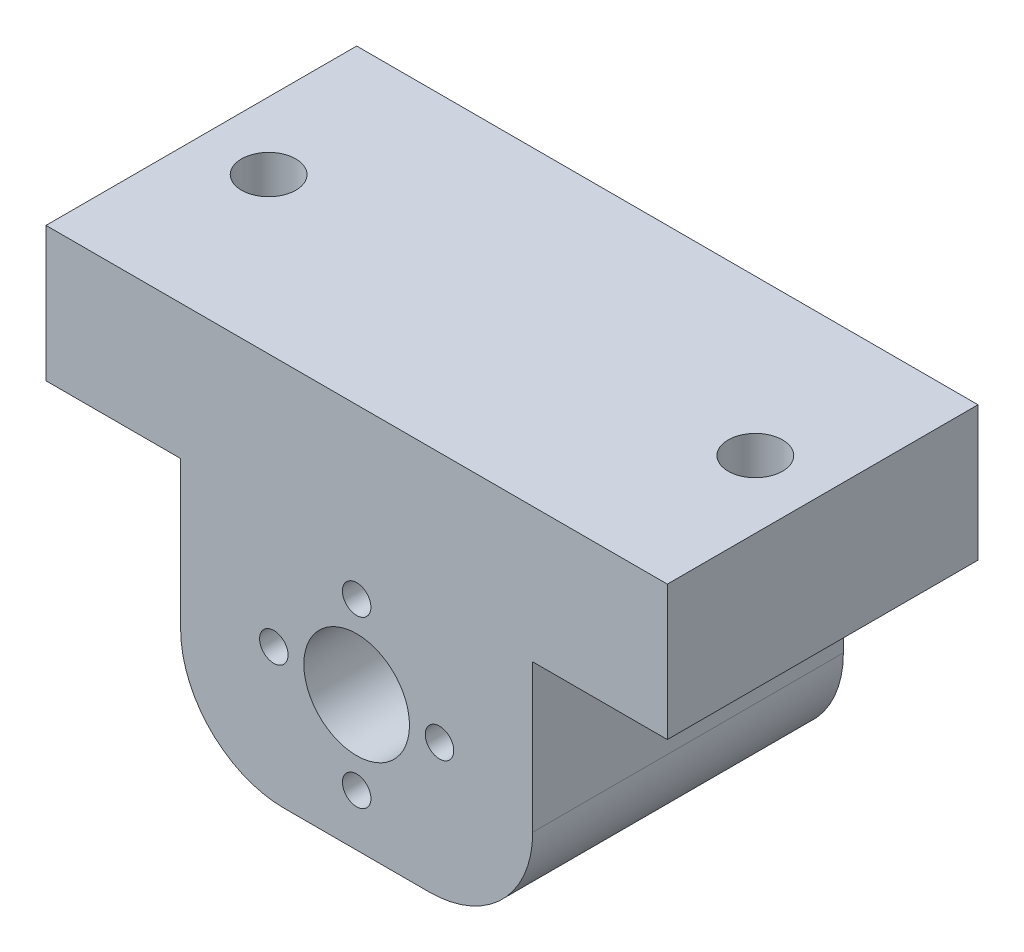
SolidWorks part; units mm, degrees
ref_plane "Alzado" through (0, 0, 0) normal (0, 0, 1) x (1, 0, 0)
ref_plane "Planta" through (0, 0, 0) normal (0, 1, 0) x (1, 0, 0)
ref_plane "Vista lateral" through (0, 0, 0) normal (1, 0, 0) x (0, 0, -1)
sketch "Croquis1" plane through (0, 0, 0) normal (0, 0, 1) x (1, 0, 0)
  line L0 (-30, 24.25) -> (30, 24.25)
  line L1 (7, -13) -> (-7, -13)
  line L2 (-30, 24.25) -> (-30, 11.25)
  line L3 (-30, 11.25) -> (-17, 11.25)
  line L4 (-17, 11.25) -> (-17, -3)
  line L5 (0, 24.25) -> (0, -13) construction
  line L6 (30, 24.25) -> (30, 11.25)
  line L7 (17, 11.25) -> (17, -3)
  line L8 (30, 11.25) -> (17, 11.25)
  circle A0 centre (0, 0) radius 5.1
  circle A1 centre (0, 0) radius 8 construction
  circle A2 centre (0, 8) radius 1.375
  circle A3 centre (8, 0) radius 1.375
  circle A4 centre (0, -8) radius 1.375
  circle A5 centre (-8, 0) radius 1.375
  arc A6 (7, -13) -> (17, -3) centre (7, -3) ccw
  arc A7 (-7, -13) -> (-17, -3) centre (-7, -3) cw
  point P6 (0, 24.25)
  point P9 (0, -13)
  point P26 (17, -13)
  point P29 (-17, -13)
  dimension "D2" = 10.2
  dimension "D7" = 2.75
  dimension "D9" = 10
  dimension "D1" = 24.25
  dimension "D3" = 13
  dimension "D4" = 13
  dimension "D5" = 60
  dimension "D6" = 17
  dimension "D8" = 8
extrude "Saliente-Extruir1" add sketch "Croquis1" along normal blind 30
sketch "Croquis2" plane through (0, 0, 0) normal (0, 0, -1) x (-1, 0, 0)
  circle A0 centre (0, 0) radius 11.75
  dimension "D1" = 23.5
extrude "Cortar-Extruir1" cut sketch "Croquis2" against normal blind 5
sketch "Croquis3" plane through (0, 11.25, 0) normal (0, -1, 0) x (1, 0, 0)
  line L0 (-23.5, 30) -> (-23.5, 15) construction
  line L1 (-30, 30) -> (-17, 30) construction
  line L2 (23.5, 30) -> (23.5, 15) construction
  line L3 (17, 30) -> (30, 30) construction
  circle A0 centre (-23.5, 15) radius 2.625
  circle A1 centre (23.5, 15) radius 2.625
  dimension "D2" = 5.25
  dimension "D1" = 15
extrude "Cortar-Extruir2" cut sketch "Croquis3" against normal through all
